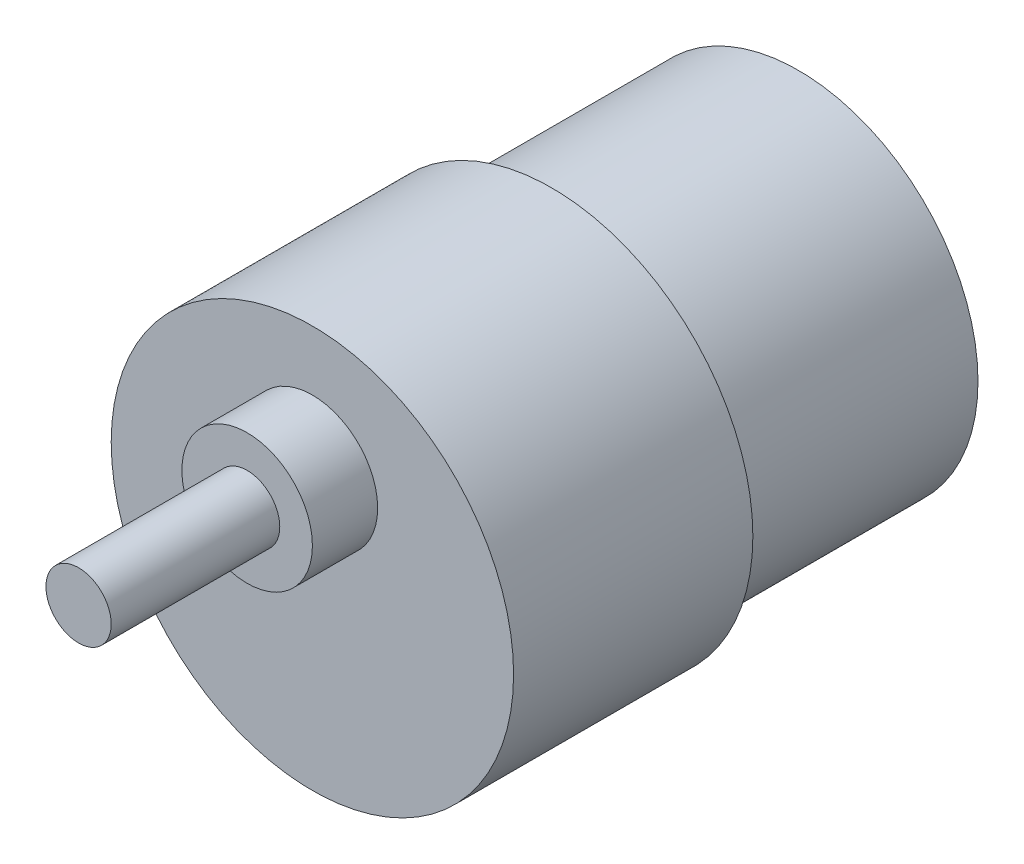
SolidWorks part; units mm, degrees
ref_plane "Front Plane" through (0, 0, 0) normal (0, 0, 1) x (1, 0, 0)
ref_plane "Top Plane" through (0, 0, 0) normal (0, 1, 0) x (1, 0, 0)
ref_plane "Right Plane" through (0, 0, 0) normal (1, 0, 0) x (0, 0, -1)
sketch "Sketch1" plane through (0, 0, 0) normal (0, 0, 1) x (1, 0, 0)
  circle A0 centre (0, 0) radius 18.5
  dimension "D1" = 37
extrude "Boss-Extrude1" add sketch "Sketch1" along normal blind 22
sketch "Sketch2" plane through (0, 0, 22) normal (0, 0, 1) x (1, 0, 0)
  circle A0 centre (0, 0) radius 15.5 construction
  circle A1 centre (0, 7) radius 6
  dimension "D1" = 31
  dimension "D2" = 7
  dimension "D3" = 12
extrude "Boss-Extrude2" add sketch "Sketch2" along normal blind 6 contours A1
sketch "Sketch3" plane through (0, 0, 28) normal (0, 0, 1) x (1, 0, 0)
  circle A0 centre (0, 7) radius 3
  circle A1 centre (0, 7) radius 6
  circle A2 centre (0, 7) radius 6
  dimension "D2" = 6
  dimension "D1" = 0
extrude "Boss-Extrude3" add sketch "Sketch3" along normal blind 15.5 contours A0
sketch "Sketch4" plane through (0, 0, 0) normal (0, 0, -1) x (-1, 0, 0)
  circle A0 centre (0, 0) radius 16.5
  dimension "D1" = 33
extrude "Boss-Extrude4" add sketch "Sketch4" along normal blind 22.7
